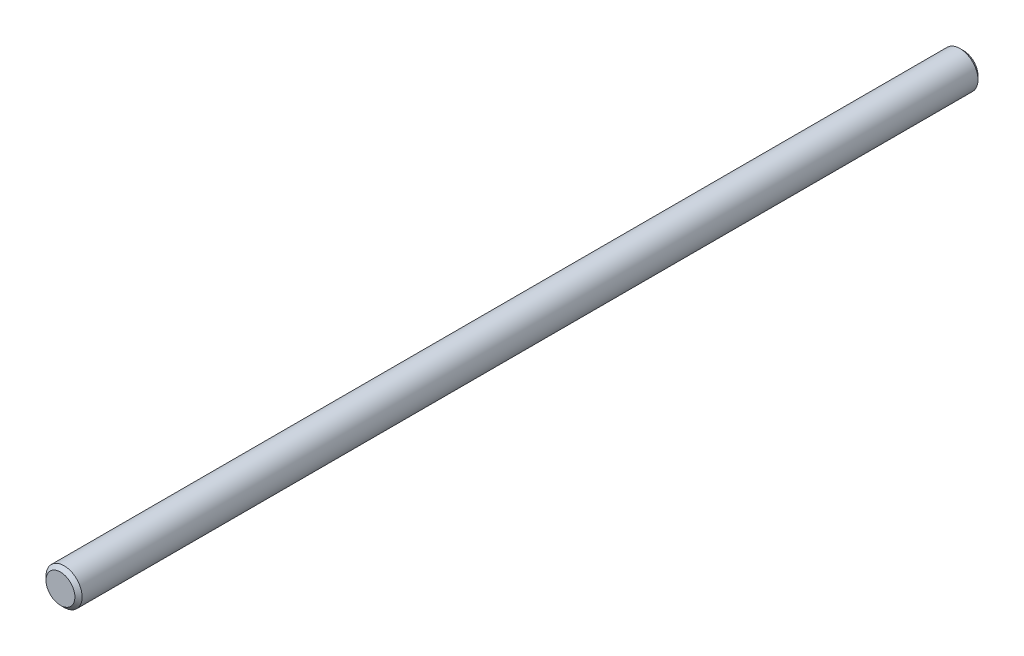
SolidWorks part; units mm, degrees
ref_plane "Front" through (0, 0, 0) normal (0, 0, 1) x (1, 0, 0)
ref_plane "Top" through (0, 0, 0) normal (0, 1, 0) x (1, 0, 0)
ref_plane "Right" through (0, 0, 0) normal (1, 0, 0) x (0, 0, -1)
sketch "Sketch1" plane through (0, 0, 0) normal (0, 0, 1) x (1, 0, 0)
  circle A0 centre (0, 0) radius 4
  dimension "dia" = 8
extrude "Extrude1" add sketch "Sketch1" along normal mid plane 200
sketch "Sketch2" plane through (0, 0, 0) normal (1, 0, 0) x (0, 0, -1)
  line L0 (100, 4) -> (-100, 4) construction
  point P0 (-100, 4)
  point P1 (100, 4)
  point P2 (-84, 4)
  point P5 (84, 4)
  dimension "D1" = 16
  dimension "D2" = 16
chamfer "Chamfer1" distance 0.8 angle 45 2 edges at (4, 0, -100) (4, 0, 100)
equation "\"D1@Chamfer1\" = \"dia@Sketch1\" * .1"
equation "\"D1@Sketch2\"=\"dia@sketch1\"*2"
equation "\"D2@Sketch2\"=\"D1@Sketch2\""
